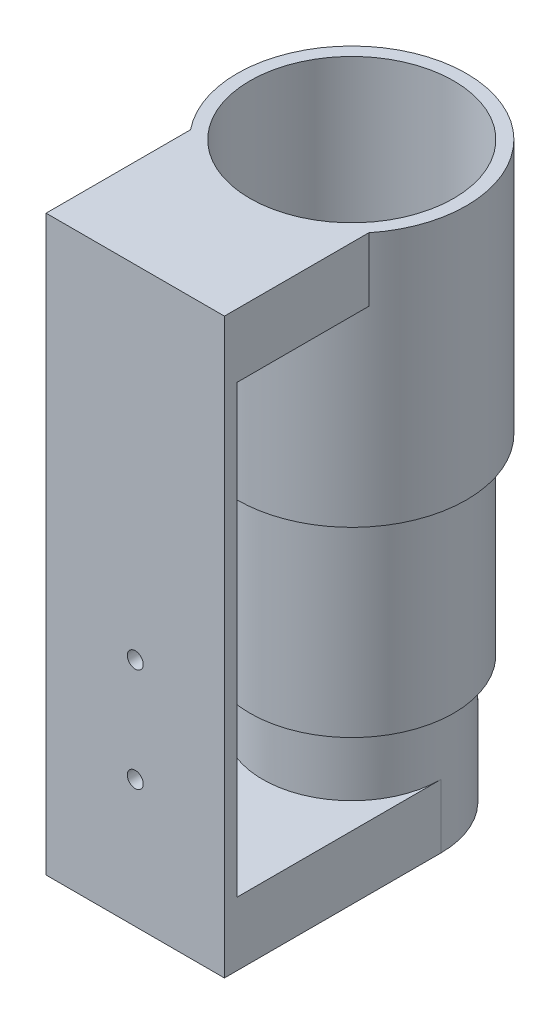
SolidWorks part; units mm, degrees
ref_plane "Front Plane" through (0, 0, 0) normal (0, 0, 1) x (1, 0, 0)
ref_plane "Top Plane" through (0, 0, 0) normal (0, 1, 0) x (1, 0, 0)
ref_plane "Right Plane" through (0, 0, 0) normal (1, 0, 0) x (0, 0, -1)
sketch "Sketch1" plane through (0, 0, 0) normal (0, 1, 0) x (1, 0, 0)
  line L1 (-3.81, -3.81) -> (3.81, -3.81)
  line L2 (-3.81, -3.81) -> (-3.81, 3.81)
  line L3 (-3.81, 3.81) -> (3.81, 3.81)
  line L4 (3.81, -3.81) -> (3.81, 3.81)
  line L5 (-3.81, -3.81) -> (3.81, 3.81) construction
  line L6 (-3.81, 3.81) -> (3.81, -3.81) construction
  circle A0 centre (0, 0) radius 15.24
  point P0 (0, 0)
extrude "Boss-Extrude1" add sketch "Sketch1" along normal blind 6.35
sketch "Sketch2" plane through (0, 0, 0) normal (0, 1, 0) x (1, 0, 0)
  circle A0 centre (0, 0) radius 15.24
  circle A1 centre (0, 0) radius 17.78
extrude "Boss-Extrude2" add sketch "Sketch2" along normal blind 25.4
sketch "Sketch5" plane through (0, 25.4, 0) normal (0, 1, 0) x (1, 0, 0)
  circle A0 centre (0, 0) radius 17.78
  circle A1 centre (0, 0) radius 20.32
extrude "Boss-Extrude3" add sketch "Sketch5" along normal blind 38.1 separate body
sketch "Sketch6" plane through (0, 63.5, 0) normal (0, 1, 0) x (1, 0, 0)
  circle A0 centre (0, 0) radius 20.32
  circle A1 centre (0, 0) radius 22.86
extrude "Boss-Extrude4" add sketch "Sketch6" along normal blind 50.8 separate body
sketch "Sketch7" plane through (0, 0, 0) normal (0, 1, 0) x (1, 0, 0)
  line L0 (-17.78, -43.1805) -> (17.78, -43.1805)
  line L3 (17.78, 0) -> (17.78, -43.1805)
  line L4 (-17.78, 0) -> (-17.78, -43.1805)
  circle A0 centre (0, 0) radius 17.78 construction
  arc A1 (17.78, 0) -> (-17.78, 0) centre (0, 0) cw
extrude "Boss-Extrude5" add sketch "Sketch7" along normal blind 12.7
sketch "Sketch9" plane through (0, 0, 43.1805) normal (0, 0, 1) x (1, 0, 0)
  line L0 (-17.78, 12.7) -> (-17.78, 114.3)
  line L1 (17.78, 12.7) -> (17.78, 114.3)
  line L2 (17.78, 114.3) -> (-17.78, 114.3)
  line L7 (-17.78, 0) -> (17.78, 0)
  line L8 (17.78, 0) -> (17.78, 12.7)
  line L9 (17.78, 12.7) -> (-17.78, 12.7)
  line L10 (-17.78, 12.7) -> (-17.78, 0)
  line L11 (-17.78, 0) -> (17.78, 0)
  line L12 (17.78, 0) -> (17.78, 12.7)
  line L14 (-17.78, 12.7) -> (-17.78, 0)
  dimension "D1" = 0
extrude "Boss-Extrude6" add sketch "Sketch9" against normal blind 2.54 contours L2 L0 L14 L11 L12 L1
sketch "Sketch10" plane through (0, 114.3, 0) normal (0, 1, 0) x (1, 0, 0)
  line L1 (-17.78, -40.6405) -> (-17.78, -14.3684)
  line L2 (17.78, -40.6405) -> (17.78, -14.3684)
  line L6 (-17.78, -43.1805) -> (17.78, -43.1805)
  line L7 (17.78, -43.1805) -> (17.78, -40.6405)
  line L8 (17.78, -40.6405) -> (-17.78, -40.6405)
  line L9 (-17.78, -40.6405) -> (-17.78, -43.1805)
  line L12 (17.78, -40.6405) -> (-17.78, -40.6405)
  circle A0 centre (0, 0) radius 22.86 construction
  arc A1 (17.78, -14.3684) -> (-17.78, -14.3684) centre (0, 0) cw
  point P10 (0, 0)
  dimension "D1" = 0
extrude "Boss-Extrude7" add sketch "Sketch10" against normal blind 12.7
sketch "Sketch13" plane through (0, 0, 43.1805) normal (0, 0, 1) x (1, 0, 0)
  circle A0 centre (0, 25.4) radius 1.5875
  circle A1 centre (0, 46.0375) radius 1.5875
extrude "Cut-Extrude1" cut sketch "Sketch13" against normal blind 10.16
